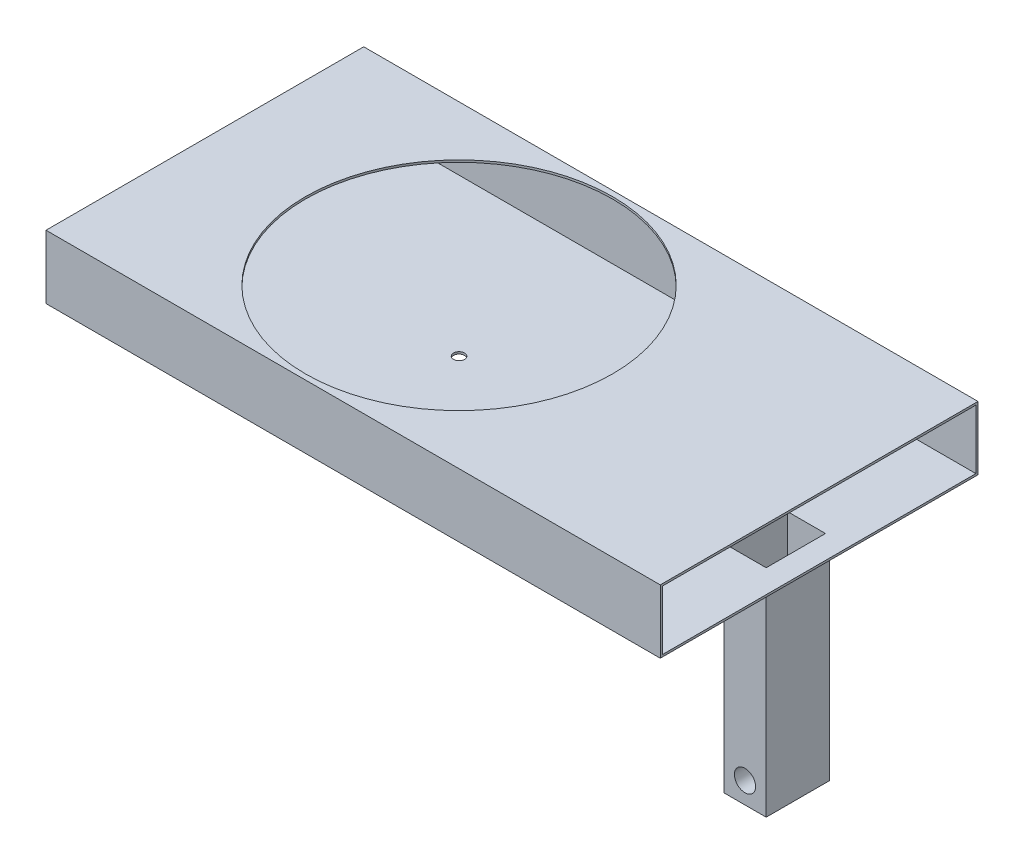
SolidWorks part; units mm, degrees
ref_plane "Front Plane" through (0, 0, 0) normal (0, 0, 1) x (1, 0, 0)
ref_plane "Top Plane" through (0, 0, 0) normal (0, 1, 0) x (1, 0, 0)
ref_plane "Right Plane" through (0, 0, 0) normal (1, 0, 0) x (0, 0, -1)
sketch "Sketch1" plane through (0, 0, 0) normal (0, 1, 0) x (1, 0, 0)
  line L1 (-368.3, 190.5) -> (368.3, 190.5)
  line L2 (-368.3, 190.5) -> (-368.3, -190.5)
  line L3 (-368.3, -190.5) -> (368.3, -190.5)
  line L4 (368.3, 190.5) -> (368.3, -190.5)
  line L5 (-368.3, 190.5) -> (368.3, -190.5) construction
  line L6 (-368.3, -190.5) -> (368.3, 190.5) construction
  point P0 (0, 0)
  dimension "D1" = 381
  dimension "D2" = 736.6
extrude "Boss-Extrude1" add sketch "Sketch1" along normal blind 76.2
sketch "Sketch2" plane through (0, 0, 0) normal (0, -1, 0) x (-1, 0, 0)
  line L0 (-368.3, -190.5) -> (-368.3, 190.5) construction
  line L1 (-292.1, -38.1) -> (-342.9, -38.1)
  line L2 (-292.1, -38.1) -> (-292.1, 38.1)
  line L3 (-292.1, 38.1) -> (-342.9, 38.1)
  line L4 (-342.9, -38.1) -> (-342.9, 38.1)
  line L5 (-292.1, -38.1) -> (-342.9, 38.1) construction
  line L6 (-292.1, 38.1) -> (-342.9, -38.1) construction
  point P0 (-317.5, 0)
  point P7 (-279.4, 6.595)
  dimension "D1" = 50.8
  dimension "D2" = 50.8
  dimension "D3" = 76.2
extrude "Boss-Extrude2" add sketch "Sketch2" along normal blind 254
sketch "Sketch3" plane through (0, 0, 38.1) normal (0, 0, 1) x (1, 0, 0)
  line L0 (342.9, -254) -> (342.9, 0) construction
  line L1 (342.9, -254) -> (292.1, -254) construction
  circle A0 centre (317.5, -228.6) radius 12.7
  dimension "D1" = 25.4
  dimension "D2" = 25.4
  dimension "D3" = 25.4
extrude "Cut-Extrude1" cut sketch "Sketch3" against normal through all
shell "Shell1" thickness 2.54
sketch "Sketch4" plane through (0, 76.2, 0) normal (0, 1, 0) x (1, 0, 0)
  line L0 (368.3, -190.5) -> (368.3, 190.5) construction
  circle A0 centre (-63.5, 0) radius 184.15
  point P2 (238.3844, 0)
  point P3 (226.9322, 0)
  point P4 (203.3812, 0)
  point P5 (170.5838, 0)
  dimension "D1" = 368.3
  dimension "D2" = 431.8
extrude "Cut-Extrude2" cut sketch "Sketch4" against normal blind 2.54
sketch "Sketch5" plane through (0, 76.2, 0) normal (0, 1, 0) x (1, 0, 0)
  circle A0 centre (-63.5, 0) radius 6.6214
  circle A1 centre (-63.5, 0) radius 184.15 construction
extrude "Cut-Extrude3" cut sketch "Sketch5" against normal blind 1219.2
